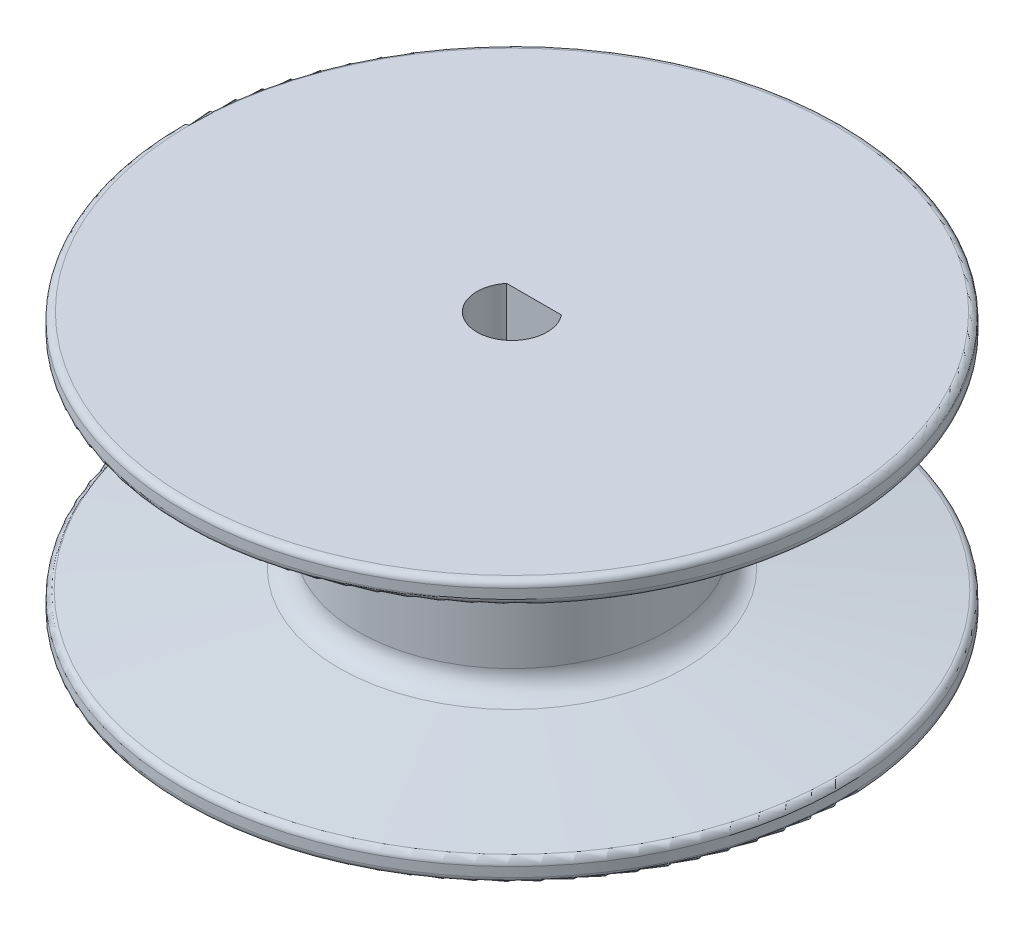
SolidWorks part; units mm, degrees
ref_plane "Front Plane" through (0, 0, 0) normal (0, 0, 1) x (1, 0, 0)
ref_plane "Top Plane" through (0, 0, 0) normal (0, 1, 0) x (1, 0, 0)
ref_plane "Right Plane" through (0, 0, 0) normal (1, 0, 0) x (0, 0, -1)
sketch "Sketch1" plane through (0, 0, 0) normal (0, 0, 1) x (1, 0, 0)
  line L0 (0, 0) -> (-15, 0)
  line L1 (-15, -1) -> (-15, 0)
  line L2 (-7, -6) -> (0, -6)
  line L3 (0, -6) -> (0, 0)
  line L4 (-15, -1) -> (-7, -2)
  line L5 (-7, -2) -> (-7, -6)
  dimension "D3" = 8
  dimension "D1" = 15
  dimension "D2" = 1
  dimension "D4" = 6
  dimension "D5" = 4
revolve "Revolve1" add sketch "Sketch1" angle 360 about L3
mirror "Mirror1" about plane through (-7, -6, 0) normal (0, 1, 0) of "Revolve1"
sketch "Sketch2" plane through (0, 0, 0) normal (0, 1, 0) x (1, 0, 0)
  line L0 (-1.249, 1) -> (1.249, 1)
  arc A0 (-1.249, 1) -> (1.249, 1) centre (0, 0) ccw
  arc A1 (1.249, 1) -> (-1.249, 1) centre (0, 0) ccw construction
  dimension "D1" = 3.2
  dimension "D2" = 1
extrude "Cut-Extrude1" cut sketch "Sketch2" along normal through all from surface at -12 starting at face at (0, -12, -15)
fillet "Fillet1" radius 1 2 edges at (0, -2, -7) (0, -10, -7)
fillet "Fillet2" radius 0.3 4 edges at (0, -12, -15) (0, -1, -15) (0, 0, -15) (0, -11, -15)
ref_plane "Plane1" through (0, 0, -11) normal (0, 0, 1) x (1, 0, 0)
sketch "Sketch3" plane through (0, 0, -11) normal (0, 0, 1) x (1, 0, 0)
  line L0 (0, -2.8828) -> (0, -9.1172)
  line L1 (7, -2.8828) -> (-7, -2.8828) construction
  line L2 (-7, -9.1172) -> (7, -9.1172) construction
  circle A0 centre (0, -6) radius 1.75
  dimension "D1" = 3.5
extrude "Cut-Extrude2" cut sketch "Sketch3" along normal blind 10.5 contours L0 A0 | L0 A0
